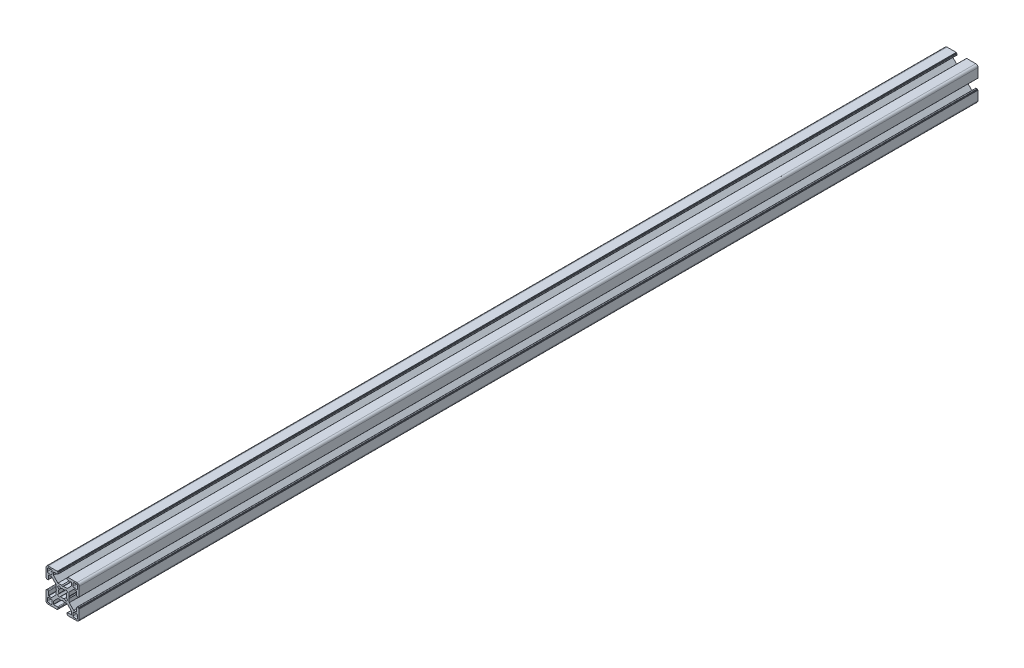
SolidWorks part; units mm, degrees
material "6061 Alloy"
ref_plane "Front" through (0, 0, 0) normal (0, 0, 1) x (1, 0, 0)
ref_plane "Top" through (0, 0, 0) normal (0, 1, 0) x (1, 0, 0)
ref_plane "Right" through (0, 0, 0) normal (1, 0, 0) x (0, 0, -1)
sketch "Sketch1" plane through (0, 0, 0) normal (0, 0, 1) x (1, 0, 0)
  line L0 (13.7, 12.7) -> (13.7, 10.5)
  line L1 (10.5, 9.5) -> (12.7, 9.5)
  line L2 (9.5, 12.7) -> (9.5, 10.5)
  line L3 (10.5, 13.7) -> (12.7, 13.7)
  line L4 (3.1359, 4.5184) -> (1.6001, 3.2806)
  line L5 (3.2806, 1.6001) -> (4.5053, 3.1547)
  line L6 (6.0045, 0.9) -> (5.4849, 0)
  line L7 (6.0045, 4.2045) -> (6.0045, 0.9)
  line L8 (0, -5.4849) -> (0.9, -6)
  line L9 (0.9, -6) -> (4.2045, -6)
  line L10 (4.2045, -6) -> (8.25, -10.05)
  line L11 (8.25, -10.05) -> (8.25, -12.6)
  line L12 (4.65, -12.8) -> (8.05, -12.8)
  line L13 (4.05, -14.3) -> (4.05, -13.4)
  line L14 (4.25, -14.5) -> (4.35, -14.5)
  line L15 (4.55, -14.8) -> (4.55, -14.7)
  line L16 (4.75, -15) -> (13, -15)
  line L17 (15, -13) -> (15, -4.75)
  line L18 (14.7, -4.55) -> (14.8, -4.55)
  line L19 (14.5, -4.35) -> (14.5, -4.25)
  line L20 (13.4, -4.05) -> (14.3, -4.05)
  line L21 (12.8, -8.05) -> (12.8, -4.65)
  line L22 (12.6, -8.25) -> (10.05, -8.25)
  line L23 (10.05, -8.25) -> (6.0045, -4.2045)
  line L24 (6.0045, -4.2045) -> (6.0045, -0.9)
  line L25 (6.0045, -0.9) -> (5.4849, 0)
  line L26 (10.05, 8.25) -> (6.0045, 4.2045)
  line L27 (12.6, 8.25) -> (10.05, 8.25)
  line L28 (12.8, 8.05) -> (12.8, 4.65)
  line L29 (13.4, 4.05) -> (14.3, 4.05)
  line L30 (14.5, 4.35) -> (14.5, 4.25)
  line L31 (14.7, 4.55) -> (14.8, 4.55)
  line L32 (15, 13) -> (15, 4.75)
  line L33 (4.75, 15) -> (13, 15)
  line L34 (4.55, 14.8) -> (4.55, 14.7)
  line L35 (4.25, 14.5) -> (4.35, 14.5)
  line L36 (4.05, 14.3) -> (4.05, 13.4)
  line L37 (4.65, 12.8) -> (8.05, 12.8)
  line L38 (8.25, 10.05) -> (8.25, 12.6)
  line L39 (4.2045, 6) -> (8.25, 10.05)
  line L40 (0.9, 6) -> (4.2045, 6)
  line L41 (0, 5.4849) -> (0.9, 6)
  line L42 (-13.7, -12.7) -> (-13.7, -10.5)
  line L43 (-10.5, -9.5) -> (-12.7, -9.5)
  line L44 (-9.5, -12.7) -> (-9.5, -10.5)
  line L45 (-10.5, -13.7) -> (-12.7, -13.7)
  line L46 (-3.1359, -4.5184) -> (-1.6001, -3.2806)
  line L47 (-3.2806, -1.6001) -> (-4.5053, -3.1547)
  line L48 (0, 5.4849) -> (-0.9, 6)
  line L49 (-0.9, 6) -> (-4.2045, 6)
  line L50 (-4.2045, 6) -> (-8.25, 10.05)
  line L51 (-8.25, 10.05) -> (-8.25, 12.6)
  line L52 (-4.65, 12.8) -> (-8.05, 12.8)
  line L53 (-4.05, 14.3) -> (-4.05, 13.4)
  line L54 (-4.25, 14.5) -> (-4.35, 14.5)
  line L55 (-4.55, 14.8) -> (-4.55, 14.7)
  line L56 (-4.75, 15) -> (-13, 15)
  line L57 (-15, 13) -> (-15, 4.75)
  line L58 (-14.7, 4.55) -> (-14.8, 4.55)
  line L59 (-14.5, 4.35) -> (-14.5, 4.25)
  line L60 (-13.4, 4.05) -> (-14.3, 4.05)
  line L61 (-12.8, 8.05) -> (-12.8, 4.65)
  line L62 (-12.6, 8.25) -> (-10.05, 8.25)
  line L63 (-10.05, 8.25) -> (-6.0045, 4.2045)
  line L64 (-6.0045, -0.9) -> (-5.4849, 0)
  line L65 (-6.0045, -4.2045) -> (-6.0045, -0.9)
  line L66 (-10.05, -8.25) -> (-6.0045, -4.2045)
  line L67 (-12.6, -8.25) -> (-10.05, -8.25)
  line L68 (-12.8, -8.05) -> (-12.8, -4.65)
  line L69 (-13.4, -4.05) -> (-14.3, -4.05)
  line L70 (-14.5, -4.35) -> (-14.5, -4.25)
  line L71 (-14.7, -4.55) -> (-14.8, -4.55)
  line L72 (-15, -13) -> (-15, -4.75)
  line L73 (-4.75, -15) -> (-13, -15)
  line L74 (-4.55, -14.8) -> (-4.55, -14.7)
  line L75 (-4.25, -14.5) -> (-4.35, -14.5)
  line L76 (-4.05, -14.3) -> (-4.05, -13.4)
  line L77 (3.2806, -1.6001) -> (4.5053, -3.1547)
  line L78 (3.1359, -4.5184) -> (1.6001, -3.2806)
  line L79 (-4.65, -12.8) -> (-8.05, -12.8)
  line L80 (-8.25, -10.05) -> (-8.25, -12.6)
  line L81 (-4.2045, -6) -> (-8.25, -10.05)
  line L82 (-0.9, -6) -> (-4.2045, -6)
  line L83 (0, -5.4849) -> (-0.9, -6)
  line L84 (10.5, -13.7) -> (12.7, -13.7)
  line L85 (9.5, -12.7) -> (9.5, -10.5)
  line L86 (10.5, -9.5) -> (12.7, -9.5)
  line L87 (13.7, -12.7) -> (13.7, -10.5)
  line L88 (-6.0045, 4.2045) -> (-6.0045, 0.9)
  line L89 (-6.0045, 0.9) -> (-5.4849, 0)
  line L90 (-3.2806, 1.6001) -> (-4.5053, 3.1547)
  line L91 (-3.1359, 4.5184) -> (-1.6001, 3.2806)
  line L92 (-10.5, 13.7) -> (-12.7, 13.7)
  line L93 (-9.5, 12.7) -> (-9.5, 10.5)
  line L94 (-10.5, 9.5) -> (-12.7, 9.5)
  line L95 (-13.7, 12.7) -> (-13.7, 10.5)
  line L96 (-23.4857, 0) -> (20.9308, 0) construction
  line L97 (0, 17.9563) -> (0, -17.361) construction
  arc A0 (13.7, 12.7) -> (12.7, 13.7) centre (12.7, 12.7) ccw
  arc A1 (12.7, 9.5) -> (13.7, 10.5) centre (12.7, 10.5) ccw
  arc A2 (9.5, 10.5) -> (10.5, 9.5) centre (10.5, 10.5) ccw
  arc A3 (10.5, 13.7) -> (9.5, 12.7) centre (10.5, 12.7) ccw
  arc A4 (1.6001, 3.2806) -> (-1.6001, 3.2806) centre (0, 0) ccw
  arc A5 (8.25, -12.6) -> (8.05, -12.8) centre (8.05, -12.6) cw
  arc A6 (4.65, -12.8) -> (4.05, -13.4) centre (4.65, -13.4) ccw
  arc A7 (4.05, -14.3) -> (4.25, -14.5) centre (4.25, -14.3) ccw
  arc A8 (4.35, -14.5) -> (4.55, -14.7) centre (4.35, -14.7) cw
  arc A9 (4.55, -14.8) -> (4.75, -15) centre (4.75, -14.8) ccw
  arc A10 (13, -15) -> (15, -13) centre (13, -13) ccw
  arc A11 (15, -4.75) -> (14.8, -4.55) centre (14.8, -4.75) ccw
  arc A12 (14.7, -4.55) -> (14.5, -4.35) centre (14.7, -4.35) cw
  arc A13 (14.5, -4.25) -> (14.3, -4.05) centre (14.3, -4.25) ccw
  arc A14 (13.4, -4.05) -> (12.8, -4.65) centre (13.4, -4.65) ccw
  arc A15 (12.8, -8.05) -> (12.6, -8.25) centre (12.6, -8.05) cw
  arc A16 (4.5053, 3.1547) -> (3.1359, 4.5184) centre (0, 0) ccw
  arc A17 (12.8, 8.05) -> (12.6, 8.25) centre (12.6, 8.05) ccw
  arc A18 (13.4, 4.05) -> (12.8, 4.65) centre (13.4, 4.65) cw
  arc A19 (14.5, 4.25) -> (14.3, 4.05) centre (14.3, 4.25) cw
  arc A20 (14.7, 4.55) -> (14.5, 4.35) centre (14.7, 4.35) ccw
  arc A21 (15, 4.75) -> (14.8, 4.55) centre (14.8, 4.75) cw
  arc A22 (13, 15) -> (15, 13) centre (13, 13) cw
  arc A23 (4.55, 14.8) -> (4.75, 15) centre (4.75, 14.8) cw
  arc A24 (4.35, 14.5) -> (4.55, 14.7) centre (4.35, 14.7) ccw
  arc A25 (4.05, 14.3) -> (4.25, 14.5) centre (4.25, 14.3) cw
  arc A26 (4.65, 12.8) -> (4.05, 13.4) centre (4.65, 13.4) cw
  arc A27 (8.25, 12.6) -> (8.05, 12.8) centre (8.05, 12.6) ccw
  arc A28 (-13.7, -12.7) -> (-12.7, -13.7) centre (-12.7, -12.7) ccw
  arc A29 (-12.7, -9.5) -> (-13.7, -10.5) centre (-12.7, -10.5) ccw
  arc A30 (-9.5, -10.5) -> (-10.5, -9.5) centre (-10.5, -10.5) ccw
  arc A31 (-10.5, -13.7) -> (-9.5, -12.7) centre (-10.5, -12.7) ccw
  arc A32 (-4.5053, -3.1547) -> (-3.1359, -4.5184) centre (0, 0) ccw
  arc A33 (-3.2806, 1.6001) -> (-3.2806, -1.6001) centre (0, 0) ccw
  arc A34 (-8.25, 12.6) -> (-8.05, 12.8) centre (-8.05, 12.6) cw
  arc A35 (-4.65, 12.8) -> (-4.05, 13.4) centre (-4.65, 13.4) ccw
  arc A36 (-4.05, 14.3) -> (-4.25, 14.5) centre (-4.25, 14.3) ccw
  arc A37 (-4.35, 14.5) -> (-4.55, 14.7) centre (-4.35, 14.7) cw
  arc A38 (-4.55, 14.8) -> (-4.75, 15) centre (-4.75, 14.8) ccw
  arc A39 (-13, 15) -> (-15, 13) centre (-13, 13) ccw
  arc A40 (-15, 4.75) -> (-14.8, 4.55) centre (-14.8, 4.75) ccw
  arc A41 (-14.7, 4.55) -> (-14.5, 4.35) centre (-14.7, 4.35) cw
  arc A42 (-14.5, 4.25) -> (-14.3, 4.05) centre (-14.3, 4.25) ccw
  arc A43 (-13.4, 4.05) -> (-12.8, 4.65) centre (-13.4, 4.65) ccw
  arc A44 (-12.8, 8.05) -> (-12.6, 8.25) centre (-12.6, 8.05) cw
  arc A45 (-4.5053, 3.1547) -> (-3.1359, 4.5184) centre (0, 0) cw
  arc A46 (-12.8, -8.05) -> (-12.6, -8.25) centre (-12.6, -8.05) ccw
  arc A47 (-13.4, -4.05) -> (-12.8, -4.65) centre (-13.4, -4.65) cw
  arc A48 (-14.5, -4.25) -> (-14.3, -4.05) centre (-14.3, -4.25) cw
  arc A49 (3.2806, 1.6001) -> (3.2806, -1.6001) centre (0, 0) cw
  arc A50 (4.5053, -3.1547) -> (3.1359, -4.5184) centre (0, 0) cw
  arc A51 (1.6001, -3.2806) -> (-1.6001, -3.2806) centre (0, 0) cw
  arc A52 (-14.7, -4.55) -> (-14.5, -4.35) centre (-14.7, -4.35) ccw
  arc A53 (-15, -4.75) -> (-14.8, -4.55) centre (-14.8, -4.75) cw
  arc A54 (-13, -15) -> (-15, -13) centre (-13, -13) cw
  arc A55 (-4.55, -14.8) -> (-4.75, -15) centre (-4.75, -14.8) cw
  arc A56 (10.5, -13.7) -> (9.5, -12.7) centre (10.5, -12.7) cw
  arc A57 (9.5, -10.5) -> (10.5, -9.5) centre (10.5, -10.5) cw
  arc A58 (12.7, -9.5) -> (13.7, -10.5) centre (12.7, -10.5) cw
  arc A59 (13.7, -12.7) -> (12.7, -13.7) centre (12.7, -12.7) cw
  arc A60 (-4.35, -14.5) -> (-4.55, -14.7) centre (-4.35, -14.7) ccw
  arc A61 (-4.05, -14.3) -> (-4.25, -14.5) centre (-4.25, -14.3) cw
  arc A62 (-4.65, -12.8) -> (-4.05, -13.4) centre (-4.65, -13.4) cw
  arc A63 (-8.25, -12.6) -> (-8.05, -12.8) centre (-8.05, -12.6) ccw
  arc A64 (-10.5, 13.7) -> (-9.5, 12.7) centre (-10.5, 12.7) cw
  arc A65 (-9.5, 10.5) -> (-10.5, 9.5) centre (-10.5, 10.5) cw
  arc A66 (-12.7, 9.5) -> (-13.7, 10.5) centre (-12.7, 10.5) cw
  arc A67 (-13.7, 12.7) -> (-12.7, 13.7) centre (-12.7, 12.7) cw
  point P81 (15, 15)
  point P82 (0, 15)
  point P203 (0, -15)
  point P204 (15, -15)
  point P206 (0, 0)
  point P207 (15, 0)
  point P219 (-15, 0)
  point P220 (-15, -15)
  point P221 (-15, 15)
  dimension "D6" = 7.3
  dimension "D7" = 11
  dimension "D1" = 30
  dimension "D2" = 15
  dimension "D3" = 30
  dimension "D4" = 8.1
  dimension "D5" = 9
  dimension "D8" = 8.1
extrude "Boss-Extrude1" add sketch "Sketch1" along normal blind 812.8
